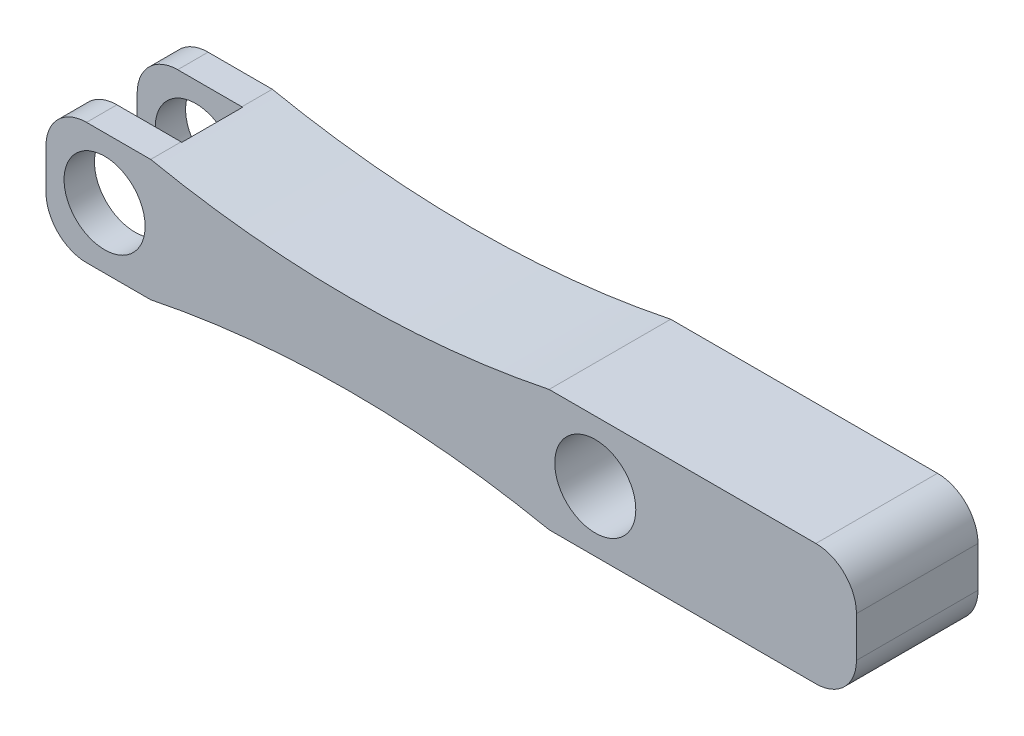
SolidWorks part; units mm, degrees
ref_plane "Front Plane" through (0, 0, 0) normal (0, 0, 1) x (1, 0, 0)
ref_plane "Top Plane" through (0, 0, 0) normal (0, 1, 0) x (1, 0, 0)
ref_plane "Right Plane" through (0, 0, 0) normal (1, 0, 0) x (0, 0, -1)
sketch "Sketch1" plane through (0, 0, 0) normal (0, 0, 1) x (1, 0, 0)
  line L1 (-53.7403, 10.2029) -> (146.2597, 10.2029)
  line L2 (-53.7403, 10.2029) -> (-53.7403, -19.7971)
  line L3 (-53.7403, -19.7971) -> (146.2597, -19.7971)
  line L4 (146.2597, 10.2029) -> (146.2597, -19.7971)
extrude "Boss-Extrude1" add sketch "Sketch1" along normal blind 30
fillet "Fillet1" radius 10 4 edges at (-53.7403, 10.2029, 15) (-53.7403, -19.7971, 15) (146.2597, -19.7971, 15) (146.2597, 10.2029, 15)
sketch "Sketch2" plane through (0, 0, 30) normal (0, 0, 1) x (1, 0, 0)
  line L1 (-27.9011, 10.2029) -> (70.4205, 10.2029)
  line L2 (-27.9011, -19.7971) -> (70.4205, -19.7971)
  line L4 (136.2597, 10.2029) -> (-43.7403, 10.2029) construction
  line L6 (-43.7403, -19.7971) -> (136.2597, -19.7971) construction
  arc A0 (-27.9011, 10.2029) -> (70.4205, 10.2029) centre (21.2597, 249.3814) ccw
  arc A1 (-27.9011, -19.7971) -> (70.4205, -19.7971) centre (21.2597, -259.0413) cw
extrude "Cut-Extrude1" cut sketch "Sketch2" against normal blind 30
sketch "Sketch3" plane through (146.2597, 0, 0) normal (1, 0, 0) x (0, 0, -1)
  line L1 (-30, 10.2029) -> (0, 10.2029) construction
  line L3 (0, -19.7971) -> (-30, -19.7971) construction
  line L4 (-22.5, 10.2029) -> (-7.5, 10.2029)
  line L5 (-22.5, 10.2029) -> (-22.5, -19.7971)
  line L6 (-22.5, -19.7971) -> (-7.5, -19.7971)
  line L7 (-7.5, 10.2029) -> (-7.5, -19.7971)
extrude "Cut-Extrude2" [suppressed] cut sketch "Sketch3" against normal blind 26
sketch "Sketch4" plane through (-53.7403, 0, 0) normal (-1, 0, 0) x (0, 0, 1)
  line L1 (0, 10.2029) -> (30, 10.2029) construction
  line L3 (30, -19.7971) -> (0, -19.7971) construction
  line L4 (7.5, 10.2029) -> (22.5, 10.2029)
  line L5 (7.5, 10.2029) -> (7.5, -19.7971)
  line L6 (7.5, -19.7971) -> (22.5, -19.7971)
  line L7 (22.5, 10.2029) -> (22.5, -19.7971)
extrude "Cut-Extrude3" cut sketch "Sketch4" against normal blind 26
sketch "Sketch5" plane through (0, 0, 30) normal (0, 0, 1) x (1, 0, 0)
  circle A0 centre (-39.2862, -4.7971) radius 10
  circle A1 centre (81.8097, -4.7971) radius 10
extrude "Cut-Extrude4" cut sketch "Sketch5" against normal blind 45
scale "Scale1" scale about centroid uniform scaling yes scale factor 4
